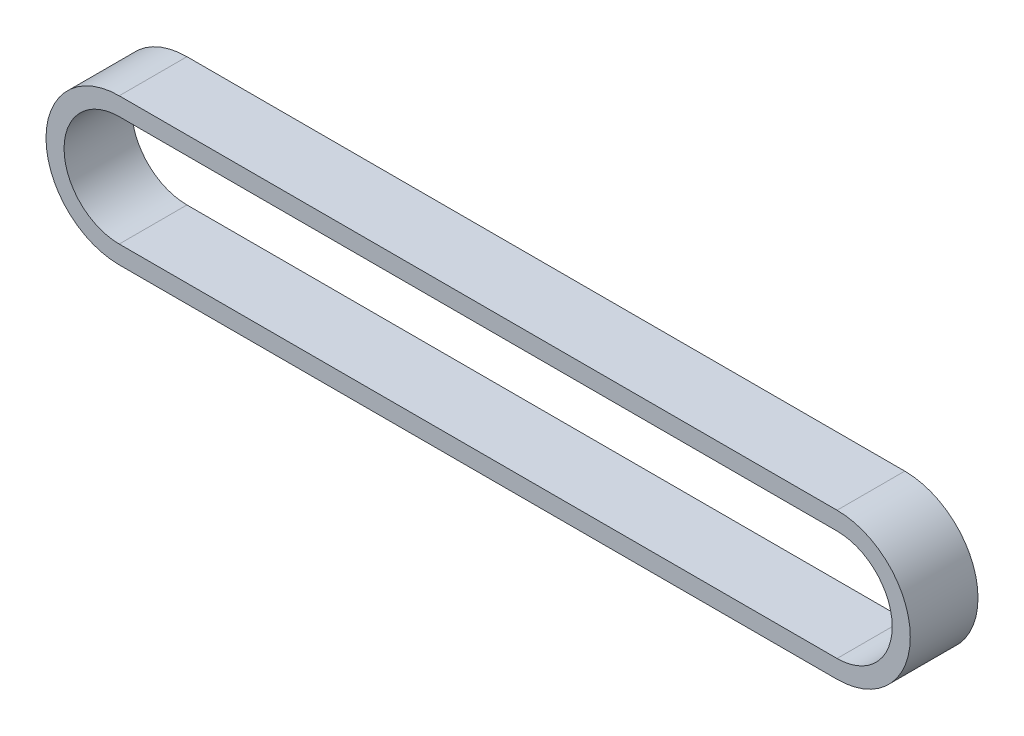
SolidWorks part; units mm, degrees
ref_plane "Front Plane" through (0, 0, 0) normal (0, 0, 1) x (1, 0, 0)
ref_plane "Top Plane" through (0, 0, 0) normal (0, 1, 0) x (1, 0, 0)
ref_plane "Right Plane" through (0, 0, 0) normal (1, 0, 0) x (0, 0, -1)
sketch "Sketch1" plane through (0, 0, 0) normal (0, 0, 1) x (1, 0, 0)
  line L0 (-39.75, 0) -> (39.75, 0) construction
  line L1 (-39.75, 6.11) -> (39.75, 6.11)
  line L2 (-39.75, -6.11) -> (39.75, -6.11)
  line L3 (-39.75, 8.11) -> (39.75, 8.11)
  line L4 (-39.75, -8.11) -> (39.75, -8.11)
  circle A0 centre (-39.75, 0) radius 6.11 construction
  circle A1 centre (39.75, 0) radius 6.11 construction
  arc A2 (-39.75, 6.11) -> (-39.75, -6.11) centre (-39.75, 0) ccw
  arc A3 (39.75, 6.11) -> (39.75, -6.11) centre (39.75, 0) cw
  circle A4 centre (-39.75, 0) radius 8.11 construction
  circle A5 centre (39.75, 0) radius 8.11 construction
  arc A6 (-39.75, 8.11) -> (-39.75, -8.11) centre (-39.75, 0) ccw
  arc A7 (39.75, 8.11) -> (39.75, -8.11) centre (39.75, 0) cw
  point P4 (0, 0)
extrude "Boss-Extrude1" add sketch "Sketch1" along normal blind 7.5
